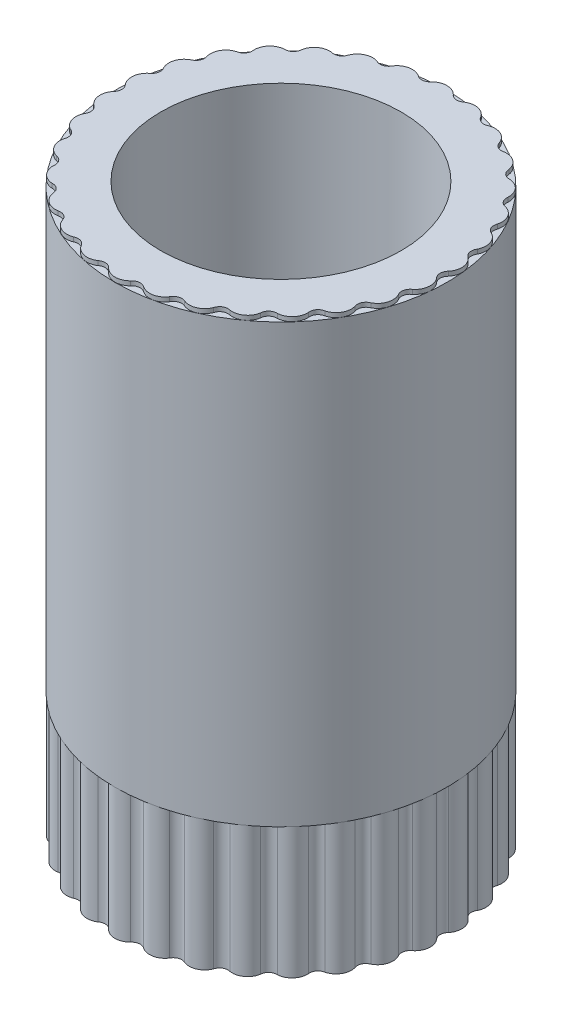
SolidWorks part; units mm, degrees
ref_plane "Front Plane" through (0, 0, 0) normal (0, 0, 1) x (1, 0, 0)
ref_plane "Top Plane" through (0, 0, 0) normal (0, 1, 0) x (1, 0, 0)
ref_plane "Right Plane" through (0, 0, 0) normal (1, 0, 0) x (0, 0, -1)
ref_plane "Plane2" through (0, 195, 0) normal (0, 1, 0) x (1, 0, 0)
sketch "Sketch4" plane through (0, 0, 0) normal (0, 0, 1) x (1, 0, 0)
sketch "Sketch5" plane through (0, 0, 0) normal (0, 0, 1) x (1, 0, 0)
  line L0 (294.0971, 237.4575) -> (406.5132, 237.4575)
  line L1 (433.6657, 143.7869) -> (509.5647, 143.7869)
  point P0 (294.0971, 237.4575)
sketch "Sketch7" plane through (0, 195, 0) normal (0, 1, 0) x (1, 0, 0)
  line L0 (469, 0) -> (474, 0) construction
  line L1 (501.0003, 0) -> (471.9998, 0) construction
  line L2 (469, 12.9436) -> (469, -45.9693) construction
  line L3 (474, 9.3679) -> (474, -40.0099) construction
  circle A0 centre (471.5, 0) radius 38 construction
  circle A1 centre (471.5, 0) radius 37 construction
  arc A2 (469, -36.9154) -> (474, -36.9154) centre (471.5, -34.4154) ccw
  arc A3 (461.3795, -35.589) -> (466.2702, -36.6285) centre (464.3446, -33.6634) ccw
  arc A4 (454.2013, -32.7071) -> (458.769, -34.7408) centre (457.502, -31.4401) ccw
  arc A5 (447.7791, -28.3958) -> (451.8242, -31.3347) centre (451.2711, -27.8427) ccw
  arc A6 (442.3937, -22.8434) -> (445.7393, -26.5591) centre (445.9243, -23.0284) ccw
  arc A7 (438.2803, -16.2927) -> (440.7803, -20.6228) centre (441.6954, -17.2077) ccw
  arc A8 (435.6188, -9.0299) -> (437.1639, -13.7851) centre (438.769, -10.635) ccw
  arc A9 (434.5255, -1.3724) -> (435.0481, -6.345) centre (437.2731, -3.5974) ccw
  arc A10 (435.0481, 6.345) -> (434.5255, 1.3724) centre (437.2731, 3.5974) ccw
  arc A11 (437.1639, 13.7851) -> (435.6188, 9.0299) centre (438.769, 10.635) ccw
  arc A12 (440.7803, 20.6228) -> (438.2803, 16.2927) centre (441.6954, 17.2077) ccw
  arc A13 (445.7393, 26.5591) -> (442.3937, 22.8434) centre (445.9243, 23.0284) ccw
  arc A14 (451.8242, 31.3347) -> (447.7791, 28.3958) centre (451.2711, 27.8427) ccw
  arc A15 (458.769, 34.7408) -> (454.2013, 32.7071) centre (457.502, 31.4401) ccw
  arc A16 (466.2702, 36.6285) -> (461.3795, 35.589) centre (464.3446, 33.6634) ccw
  arc A17 (474, 36.9154) -> (469, 36.9154) centre (471.5, 34.4154) ccw
  arc A18 (481.6205, 35.589) -> (476.7298, 36.6285) centre (478.6554, 33.6634) ccw
  arc A19 (488.7987, 32.7071) -> (484.231, 34.7408) centre (485.498, 31.4401) ccw
  arc A20 (495.2209, 28.3958) -> (491.1758, 31.3347) centre (491.7289, 27.8427) ccw
  arc A21 (500.6064, 22.8434) -> (497.2607, 26.5591) centre (497.0757, 23.0284) ccw
  arc A22 (504.7197, 16.2927) -> (502.2197, 20.6228) centre (501.3047, 17.2077) ccw
  arc A23 (507.3812, 9.0299) -> (505.8361, 13.7851) centre (504.231, 10.635) ccw
  arc A24 (508.4745, 1.3724) -> (507.9519, 6.345) centre (505.7269, 3.5974) ccw
  arc A25 (507.9519, -6.345) -> (508.4745, -1.3724) centre (505.7269, -3.5974) ccw
  arc A26 (505.8361, -13.7851) -> (507.3812, -9.0299) centre (504.231, -10.635) ccw
  arc A27 (502.2197, -20.6228) -> (504.7197, -16.2927) centre (501.3047, -17.2077) ccw
  arc A28 (497.2607, -26.5591) -> (500.6064, -22.8434) centre (497.0757, -23.0284) ccw
  arc A29 (491.1758, -31.3347) -> (495.2209, -28.3958) centre (491.7289, -27.8427) ccw
  arc A30 (484.231, -34.7408) -> (488.7987, -32.7071) centre (485.498, -31.4401) ccw
  arc A31 (476.7298, -36.6285) -> (481.6205, -35.589) centre (478.6554, -33.6634) ccw
  arc A32 (434.5255, 1.3724) -> (434.5255, -1.3724) centre (433.1531, 0) cw
  arc A33 (435.6188, 9.0299) -> (435.0481, 6.345) centre (433.991, 7.9728) cw
  arc A34 (438.2803, 16.2927) -> (437.1639, 13.7851) centre (436.4683, 15.5971) cw
  arc A35 (442.3937, 22.8434) -> (440.7803, 20.6228) centre (440.4767, 22.5398) cw
  arc A36 (447.7791, 28.3958) -> (445.7393, 26.5591) centre (445.8409, 28.4973) cw
  arc A37 (454.2013, 32.7071) -> (451.8242, 31.3347) centre (452.3265, 33.2094) cw
  arc A38 (461.3795, 35.589) -> (458.769, 34.7408) centre (459.6501, 36.4701) cw
  arc A39 (469, 36.9154) -> (466.2702, 36.6285) centre (467.4917, 38.1369) cw
  arc A40 (476.7298, 36.6285) -> (474, 36.9154) centre (475.5084, 38.1369) cw
  arc A41 (484.231, 34.7408) -> (481.6205, 35.589) centre (483.3499, 36.4701) cw
  arc A42 (491.1758, 31.3347) -> (488.7987, 32.7071) centre (490.6735, 33.2094) cw
  arc A43 (497.2607, 26.5591) -> (495.2209, 28.3958) centre (497.1591, 28.4973) cw
  arc A44 (502.2197, 20.6228) -> (500.6064, 22.8434) centre (502.5233, 22.5398) cw
  arc A45 (505.8361, 13.7851) -> (504.7197, 16.2927) centre (506.5317, 15.5971) cw
  arc A46 (507.9519, 6.345) -> (507.3812, 9.0299) centre (509.009, 7.9728) cw
  arc A47 (508.4745, -1.3724) -> (508.4745, 1.3724) centre (509.847, 0) cw
  arc A48 (507.3812, -9.0299) -> (507.9519, -6.345) centre (509.009, -7.9728) cw
  arc A49 (504.7197, -16.2927) -> (505.8361, -13.7851) centre (506.5317, -15.5971) cw
  arc A50 (500.6064, -22.8434) -> (502.2197, -20.6228) centre (502.5233, -22.5398) cw
  arc A51 (495.2209, -28.3958) -> (497.2607, -26.5591) centre (497.1591, -28.4973) cw
  arc A52 (488.7987, -32.7071) -> (491.1758, -31.3347) centre (490.6735, -33.2094) cw
  arc A53 (481.6205, -35.589) -> (484.231, -34.7408) centre (483.3499, -36.4701) cw
  arc A54 (474, -36.9154) -> (476.7298, -36.6285) centre (475.5084, -38.1369) cw
  arc A55 (466.2702, -36.6285) -> (469, -36.9154) centre (467.4917, -38.1369) cw
  arc A56 (458.769, -34.7408) -> (461.3795, -35.589) centre (459.6501, -36.4701) cw
  arc A57 (451.8242, -31.3347) -> (454.2013, -32.7071) centre (452.3265, -33.2094) cw
  arc A58 (445.7393, -26.5591) -> (447.7791, -28.3958) centre (445.8409, -28.4973) cw
  arc A59 (440.7803, -20.6228) -> (442.3937, -22.8434) centre (440.4767, -22.5398) cw
  arc A60 (437.1639, -13.7851) -> (438.2803, -16.2927) centre (436.4683, -15.5971) cw
  arc A61 (435.0481, -6.345) -> (435.6188, -9.0299) centre (433.991, -7.9728) cw
  circle A62 centre (471.5, 0) radius 27.4931
  point P9 (471.5, 0)
  point P106 (471.5, 0)
  point P194 (471.5, 0)
  dimension "D1" = 30
  dimension "D2" = 30
extrude "Boss-Extrude2" add sketch "Sketch7" against normal blind 130 and the other way blind 1
sketch "Sketch11" plane through (0, 195, 0) normal (0, 1, 0) x (1, 0, 0)
  circle A0 centre (471.5, 0) radius 38
  circle A1 centre (471.5, 0) radius 27.4931
extrude "Cut-Extrude1" cut sketch "Sketch11" against normal blind 100
sketch "Sketch12" plane through (0, 195, 0) normal (0, 1, 0) x (1, 0, 0)
  circle A0 centre (471.5, 0) radius 38
  circle A1 centre (471.5, 0) radius 27.4931
extrude "Boss-Extrude3" add sketch "Sketch12" against normal blind 100
